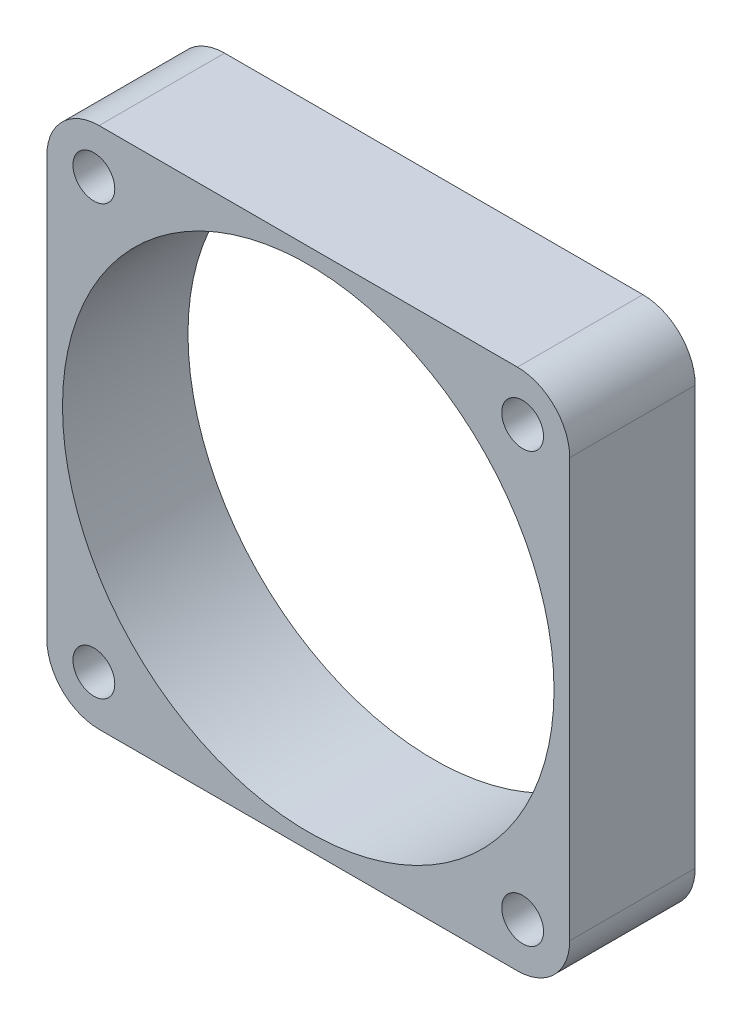
SolidWorks part; units mm, degrees
ref_plane "前视基准面" through (0, 0, 0) normal (0, 0, 1) x (1, 0, 0)
ref_plane "上视基准面" through (0, 0, 0) normal (0, 1, 0) x (1, 0, 0)
ref_plane "右视基准面" through (0, 0, 0) normal (1, 0, 0) x (0, 0, -1)
sketch "草图1" plane through (0, 0, 0) normal (0, 0, 1) x (1, 0, 0)
  line L0 (-1.2062, -43.8665) -> (-51.2062, 6.1335) construction
  line L1 (-51.2062, 6.1335) -> (-1.2062, 6.1335)
  line L2 (-51.2062, 6.1335) -> (-51.2062, -43.8665)
  line L3 (-51.2062, -43.8665) -> (-1.2062, -43.8665)
  line L4 (-1.2062, 6.1335) -> (-1.2062, -43.8665)
  line L5 (-51.2062, -43.8665) -> (-1.2062, 6.1335) construction
  circle A0 centre (-46.7062, -39.3665) radius 2
  circle A1 centre (-5.7062, -39.3665) radius 2
  circle A2 centre (-5.7062, 1.6335) radius 2
  circle A3 centre (-46.7062, 1.6335) radius 2
  circle A4 centre (-26.2062, -18.8665) radius 23.5
  point P13 (-26.2062, -18.8665)
  dimension "D3" = 4
  dimension "D8" = 47
  dimension "D1" = 50
  dimension "D2" = 50
  dimension "D4" = 4.5
  dimension "D5" = 4.5
  dimension "D6" = 4.5
  dimension "4.95" = 4.5
extrude "凸台-拉伸1" add sketch "草图1" along normal blind 12
fillet "圆角1" radius 5 4 edges at (-51.2062, -43.8665, 6) (-51.2062, 6.1335, 6) (-1.2062, -43.8665, 6) (-1.2062, 6.1335, 6)
